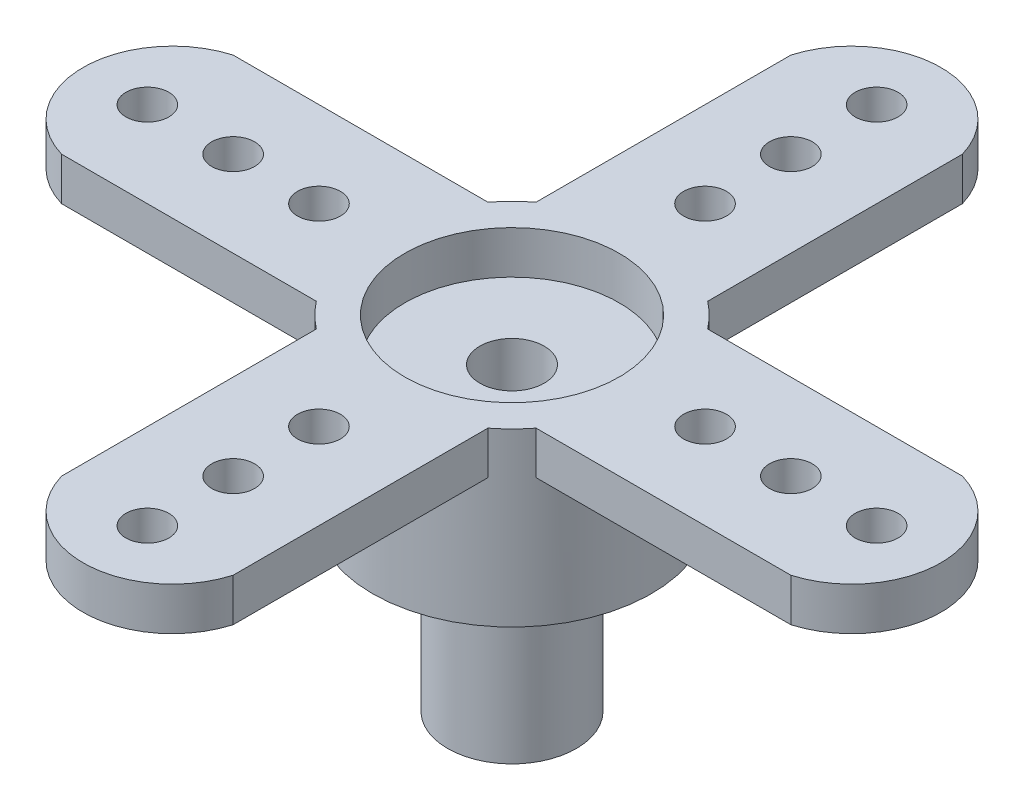
SolidWorks part; units mm, degrees
ref_plane "Plan de face" through (0, 0, 0) normal (0, 0, 1) x (1, 0, 0)
ref_plane "Plan de dessus" through (0, 0, 0) normal (0, 1, 0) x (1, 0, 0)
ref_plane "Plan de droite" through (0, 0, 0) normal (1, 0, 0) x (0, 0, -1)
sketch "Esquisse1" plane through (0, 0, 0) normal (0, 1, 0) x (1, 0, 0)
  circle A0 centre (0, 0) radius 1.5
  dimension "D1" = 3
extrude "Boss.-Extru.1" add sketch "Esquisse1" along normal blind 4
ref_plane "Plan1" through (0, 4, 0) normal (0, 1, 0) x (1, 0, 0)
sketch "Esquisse2" plane through (0, 4, 0) normal (0, 1, 0) x (1, 0, 0)
  circle A0 centre (0, 0) radius 3.25
  dimension "D1" = 6.5
extrude "Boss.-Extru.2" add sketch "Esquisse2" along normal blind 4
ref_plane "Plan2" through (0, 7, 0) normal (0, 1, 0) x (1, 0, 0)
sketch "Esquisse3" plane through (0, 8, 0) normal (0, 1, 0) x (1, 0, 0)
  line L0 (-2, -10) -> (-2, -8.5) construction
  line L1 (-2, -10) -> (2, -10)
  line L2 (-2, -10) -> (-2, 0)
  line L3 (-2, 0) -> (2, 0)
  line L4 (2, -10) -> (2, 0)
  line L5 (-2, -10) -> (2, 0) construction
  line L6 (-2, 0) -> (2, -10) construction
  line L7 (-2, -8.5) -> (2, -8.5) construction
  arc A0 (-2, -8.5) -> (2, -8.5) centre (0, -7.9167) ccw
  point P0 (0, -5)
  circle M3 centre (0, 0) radius 3.25
  dimension "D1" = 4
  dimension "D2" = 10
  dimension "D3" = 1.5
extrude "Boss.-Extru.3" add sketch "Esquisse3" against normal blind 1 contours A0 L4 L2 M3
sketch "Esquisse4" plane through (0, 0, 0) normal (0, 0, 1) x (1, 0, 0)
  line L0 (-0.002, -0.4154) -> (11.8474, 49999.5831) construction
  line L1 (2, 8) -> (-2, 8) construction
  point P4 (0, 8)
pattern_circular "Répétition circulaire6" count 4 over 360 about axis through (0, 0, 0) along (0, 1, 0) of "Boss.-Extru.3"
sketch "Esquisse5" plane through (0, 8, 0) normal (0, 1, 0) x (1, 0, 0)
  line L0 (0, -10) -> (0, -8.5) construction
  arc A0 (-2, -8.5) -> (2, -8.5) centre (0, -7.9167) ccw construction
  circle A1 centre (0, -8.5) radius 0.5
  dimension "D2" = 1
  dimension "D1" = 1.5
extrude "Enlèv. mat.-Extru.1" cut sketch "Esquisse5" against normal blind 1 contours A1
pattern_linear "Répétition linéaire1" count 3 spacing 2 along (0, 0, -1) of "Enlèv. mat.-Extru.1"
pattern_circular "Répétition circulaire7" count 4 over 360 about axis through (0, 0, 0) along (0, 1, 0) of "Enlèv. mat.-Extru.1", "Répétition linéaire1"
sketch "Esquisse6" plane through (0, 8, 0) normal (0, 1, 0) x (1, 0, 0)
  circle A0 centre (0, 0) radius 2.5
  dimension "D1" = 5
extrude "Enlèv. mat.-Extru.2" cut sketch "Esquisse6" against normal blind 1
sketch "Esquisse7" plane through (0, 7, 0) normal (0, 1, 0) x (1, 0, 0)
  circle A0 centre (0, 0) radius 0.75
  dimension "D1" = 1.5
extrude "Enlèv. mat.-Extru.3" cut sketch "Esquisse7" against normal blind 2
